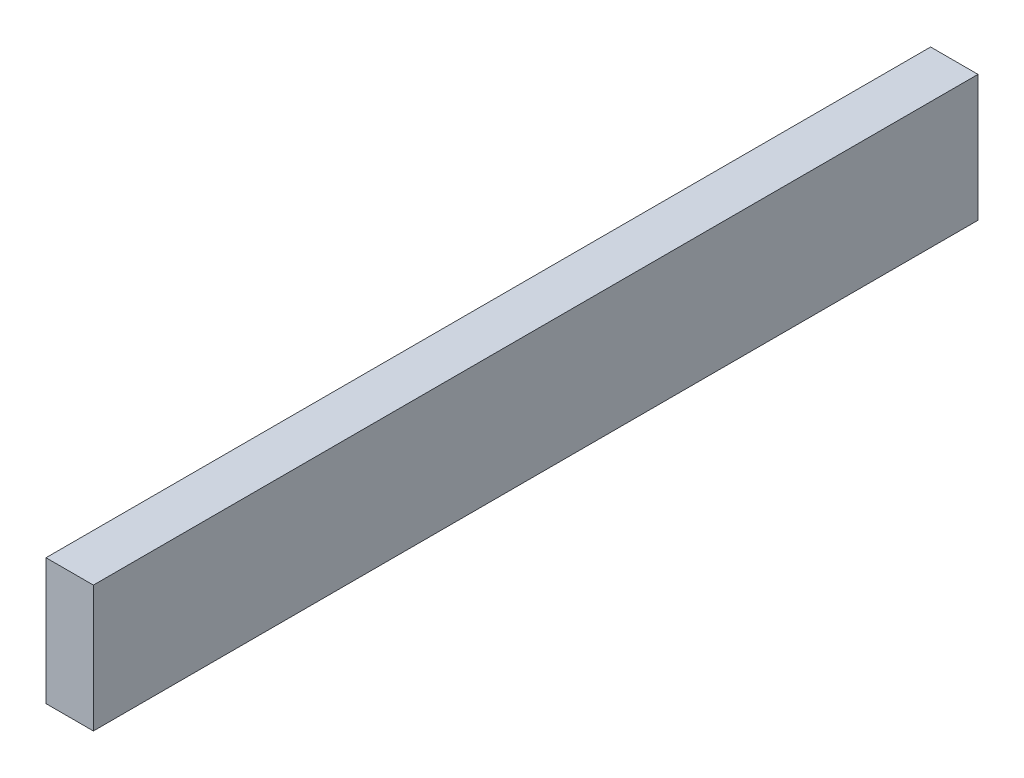
SolidWorks part; units mm, degrees
material "Pine"
ref_plane "Front Plane" through (0, 0, 0) normal (0, 0, 1) x (1, 0, 0)
ref_plane "Top Plane" through (0, 0, 0) normal (0, 1, 0) x (1, 0, 0)
ref_plane "Right Plane" through (0, 0, 0) normal (1, 0, 0) x (0, 0, -1)
sketch "Sketch1" plane through (0, 0, 0) normal (0, 1, 0) x (1, 0, 0)
  line L1 (-9.525, -177.8) -> (9.525, -177.8)
  line L2 (-9.525, -177.8) -> (-9.525, 177.8)
  line L3 (-9.525, 177.8) -> (9.525, 177.8)
  line L4 (9.525, -177.8) -> (9.525, 177.8)
  line L5 (-9.525, -177.8) -> (9.525, 177.8) construction
  line L6 (-9.525, 177.8) -> (9.525, -177.8) construction
  point P0 (0, 0)
  dimension "D1" = 355.6
  dimension "D2" = 19.05
extrude "Boss-Extrude1" add sketch "Sketch1" against normal blind 50.8
sketch "Sketch2" plane through (9.525, 0, 0) normal (1, 0, 0) x (0, 0, -1)
  line L0 (177.8, -50.8) -> (177.8, 0) construction
  line L1 (-177.8, -50.8) -> (-177.8, 0) construction
  circle A0 centre (25.4, -25.4) radius 6.35
  circle A1 centre (-88.9, -25.4) radius 6.35
  point P5 (177.8, -25.4)
  dimension "D1" = 12.7
  dimension "D2" = 152.4
  dimension "D3" = 88.9
extrude "Cut-Extrude1" [suppressed] cut sketch "Sketch2" against normal through all
